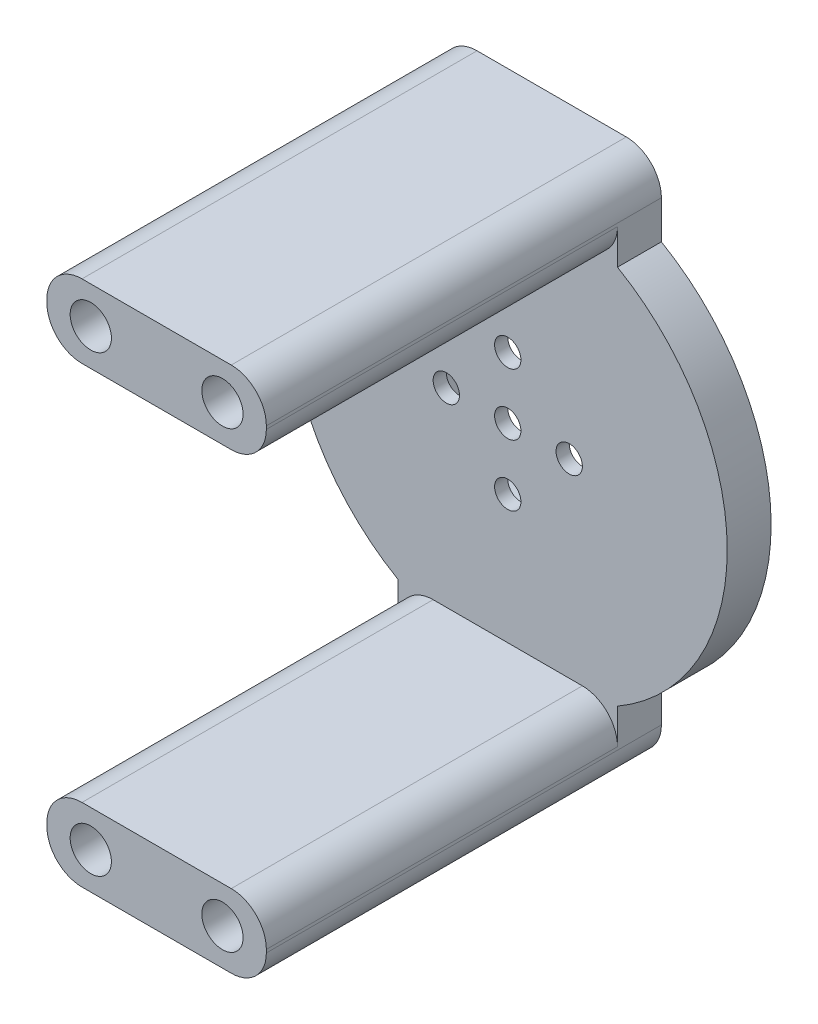
SolidWorks part; units mm, degrees
ref_plane "Front Plane" through (0, 0, 0) normal (0, 0, 1) x (1, 0, 0)
ref_plane "Top Plane" through (0, 0, 0) normal (0, 1, 0) x (1, 0, 0)
ref_plane "Right Plane" through (0, 0, 0) normal (1, 0, 0) x (0, 0, -1)
sketch "Sketch1" plane through (0, 0, 0) normal (0, 0, 1) x (1, 0, 0)
  line L1 (-12.5, -30) -> (12.5, -30)
  line L2 (-12.5, -30) -> (-12.5, 30)
  line L3 (-12.5, 30) -> (12.5, 30)
  line L4 (12.5, -30) -> (12.5, 30)
  line L5 (-12.5, -30) -> (12.5, 30) construction
  line L6 (-12.5, 30) -> (12.5, -30) construction
  circle A0 centre (0, 0) radius 25
  circle A1 centre (0, 0) radius 10.5 construction
  circle A2 centre (0, 0) radius 7 construction
  circle A3 centre (0, 7) radius 1.5
  circle A4 centre (7, 0) radius 1.5
  circle A5 centre (0, -7) radius 1.5
  circle A6 centre (-7, 0) radius 1.5
  circle A7 centre (0, 0) radius 1.5
  dimension "D1" = 50
  dimension "D2" = 21
  dimension "D3" = 14
  dimension "D4" = 3
  dimension "D6" = 3
  dimension "D7" = 25
  dimension "D8" = 60
  dimension "D5" = 4
extrude "Boss-Extrude1" add sketch "Sketch1" along normal blind 5 contours L2 A0 | L4 A0 L2 A7 A6 A5 A4 A3 | A0 L4 L3 L2 | A0 L2 L1 L4 | L4 A0
sketch "Sketch3" plane through (0, 0, 0) normal (0, 0, -1) x (-1, 0, 0)
  circle A0 centre (0, 0) radius 10.5
  dimension "D1" = 21
extrude "Cut-Extrude2" cut sketch "Sketch3" against normal blind 3.5
sketch "Sketch4" plane through (0, 0, 5) normal (0, 0, 1) x (1, 0, 0)
  line L1 (-12.5, 30) -> (12.5, 30)
  line L2 (-12.5, 30) -> (-12.5, 21.6506)
  line L3 (-12.5, 21.6506) -> (12.5, 21.6506)
  line L4 (12.5, 30) -> (12.5, 21.6506)
  line L5 (-12.5, -30) -> (12.5, -30)
  line L6 (-12.5, -30) -> (-12.5, -21.6506)
  line L7 (-12.5, -21.6506) -> (12.5, -21.6506)
  line L8 (12.5, -30) -> (12.5, -21.6506)
extrude "Boss-Extrude2" add sketch "Sketch4" along normal blind 40
fillet "Fillet1" radius 4 8 edges at (-12.5, -30, 22.5) (-12.5, -21.6506, 25) (12.5, -30, 22.5) (12.5, -21.6506, 25) (12.5, 21.6506, 25) (12.5, 30, 22.5) (-12.5, 21.6506, 25) (-12.5, 30, 22.5)
sketch "Sketch5" plane through (0, 0, 45) normal (0, 0, 1) x (1, 0, 0)
  line L0 (-12.5, 26) -> (-12.5, 25.6506) construction
  line L1 (-8.5, 21.6506) -> (8.5, 21.6506) construction
  line L2 (-2.9985, 0) -> (3.2146, 0) construction
  line L4 (0, -2.6502) -> (0, 3.6414) construction
  circle A0 centre (-7.5, 25.8253) radius 2.35
  circle A1 centre (7.5, 25.8253) radius 2.35
  circle A2 centre (7.5, -25.8253) radius 2.35
  circle A3 centre (-7.5, -25.8253) radius 2.35
  dimension "D1" = 4.7
  dimension "D2" = 5
  dimension "D3" = 4.1747
  dimension "D4" = 0
extrude "Cut-Extrude3" cut sketch "Sketch5" against normal blind 6
